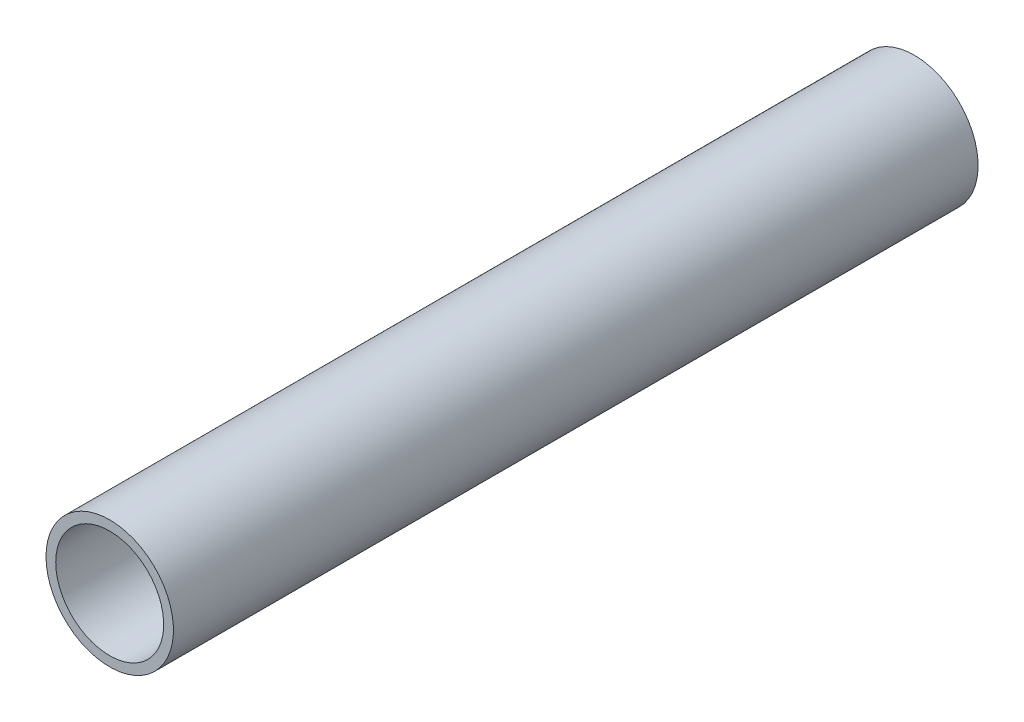
SolidWorks part; units mm, degrees
ref_plane "Front Plane" through (0, 0, 0) normal (1, 0, 0) x (0, 1, 0)
ref_plane "Top Plane" through (0, 0, 0) normal (0, 0, 1) x (0, 1, 0)
ref_plane "Right Plane" through (0, 0, 0) normal (0, 1, 0) x (-1, 0, 0)
sketch "Sketch2" plane through (0, 0, 0) normal (0, 0, 1) x (0, 1, 0)
  line L0 (0, 0) -> (24.13, 0) construction
  circle A0 centre (0, 0) radius 24.13
  circle A1 centre (0, 0) radius 20.447
  dimension "D1" = 40.894
  dimension "D2" = 48.26
extrude "base" add sketch "Sketch2" along normal blind 304.8
sketch "Sketch3" plane through (0, 0, 0) normal (0, 0, -1) x (1, 0, 0)
  circle A0 centre (0, 0) radius 21.9075
  circle A1 centre (0, 0) radius 20.447
  circle A2 centre (0, 0) radius 20.447 construction
  dimension "D1" = 43.815
extrude "snap_ring_groove" cut sketch "Sketch3" against normal blind 1.7272 from offset 6.35
